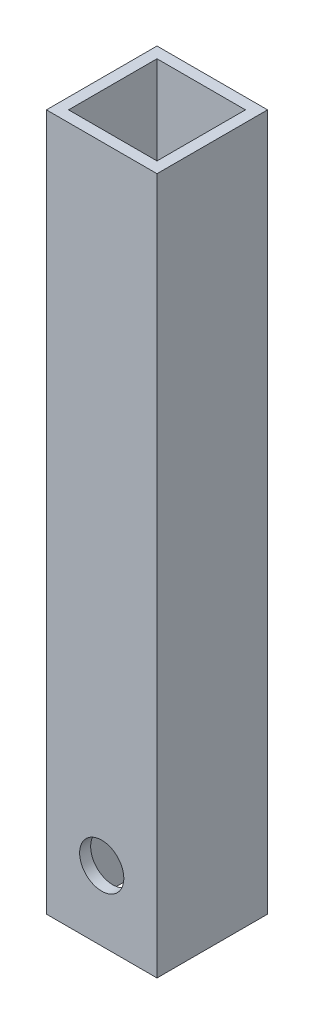
SolidWorks part; units mm, degrees
material "Brass"
ref_plane "Front Plane" through (0, 0, 0) normal (0, 0, 1) x (1, 0, 0)
ref_plane "Top Plane" through (0, 0, 0) normal (0, 1, 0) x (1, 0, 0)
ref_plane "Right Plane" through (0, 0, 0) normal (1, 0, 0) x (0, 0, -1)
sketch "Sketch1" plane through (0, 0, 0) normal (0, 1, 0) x (1, 0, 0)
  line L1 (-1.9844, 1.9844) -> (1.9844, 1.9844)
  line L2 (-1.9844, 1.9844) -> (-1.9844, -1.9844)
  line L3 (-1.9844, -1.9844) -> (1.9844, -1.9844)
  line L4 (1.9844, 1.9844) -> (1.9844, -1.9844)
  line L5 (-1.9844, 1.9844) -> (1.9844, -1.9844) construction
  line L6 (-1.9844, -1.9844) -> (1.9844, 1.9844) construction
  point P0 (0, 0)
  dimension "D1" = 3.9688
  dimension "D2" = 3.9688
extrude "Boss-Extrude1" add sketch "Sketch1" along normal mid plane 25
sketch "Sketch2" plane through (0, 12.5, 0) normal (0, 1, 0) x (1, 0, 0)
  line L1 (-1.5875, 1.5875) -> (1.5875, 1.5875)
  line L2 (-1.5875, 1.5875) -> (-1.5875, -1.5875)
  line L3 (-1.5875, -1.5875) -> (1.5875, -1.5875)
  line L4 (1.5875, 1.5875) -> (1.5875, -1.5875)
  line L5 (-1.5875, 1.5875) -> (1.5875, -1.5875) construction
  line L6 (-1.5875, -1.5875) -> (1.5875, 1.5875) construction
  point P0 (0, 0)
  dimension "D1" = 3.175
  dimension "D2" = 3.175
extrude "Cut-Extrude1" cut sketch "Sketch2" against normal through all
sketch "Sketch3" plane through (0, 0, 0) normal (0, 0, 1) x (1, 0, 0)
  line L0 (-1.9844, -12.5) -> (1.9844, -12.5) construction
  circle A0 centre (0, -10) radius 0.7937
  point P2 (0, -12.5)
  dimension "D1" = 1.5875
  dimension "D2" = 2.5
extrude "Cut-Extrude2" cut sketch "Sketch3" against normal through all and the other way through all
